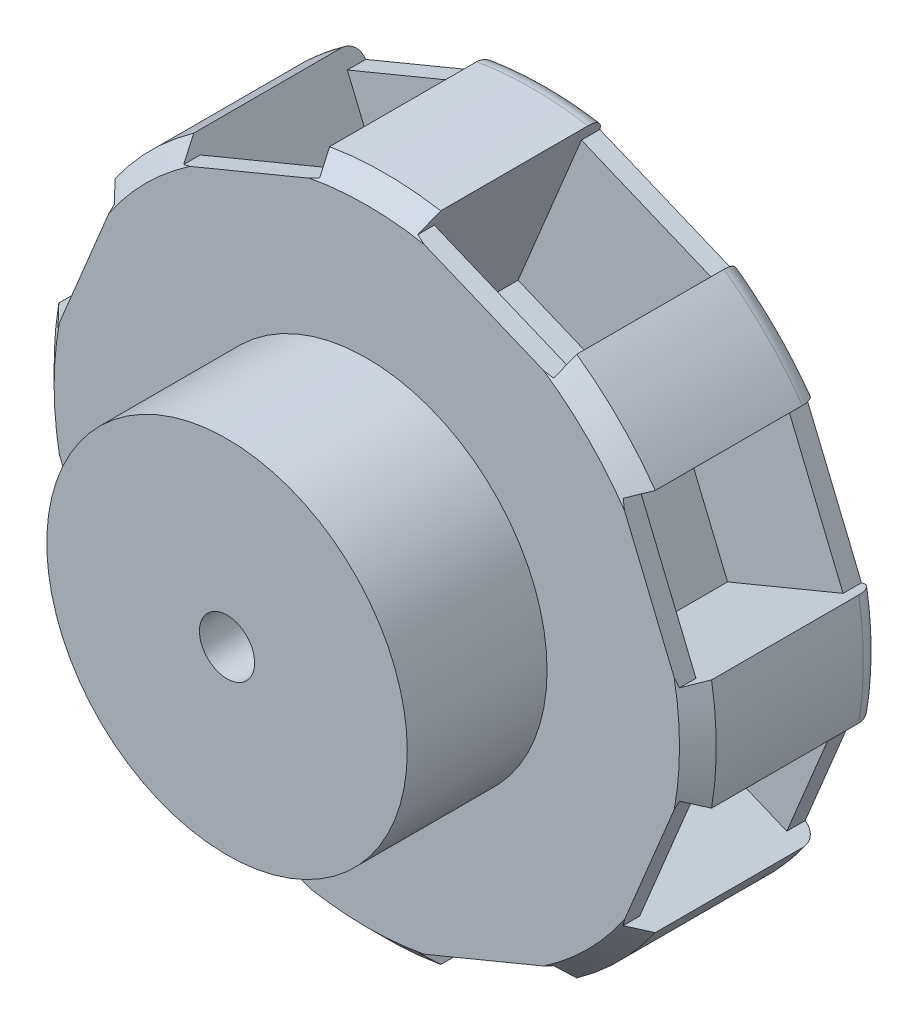
SolidWorks part; units mm, degrees
other "Marca1"
sketch "Croquis12" plane through (-138.4104, -50.431, 0) normal (-0.0114, -0.0085, -0.9999) x (-0.9379, -0.3466, 0.0137)
ref_plane "Alzado" through (0, 0, 0) normal (0, 0, 1) x (1, 0, 0)
ref_plane "Planta" through (0, 0, 0) normal (0, 1, 0) x (1, 0, 0)
ref_plane "Vista lateral" through (0, 0, 0) normal (1, 0, 0) x (0, 0, -1)
sketch "Croquis1" plane through (0, 0, 0) normal (0, 0, 1) x (1, 0, 0)
  circle A0 centre (-48.4104, 39.569) radius 90
  circle A1 centre (-48.4104, 39.569) radius 7.5
  dimension "D1" = 180
  dimension "D2" = 15
extrude "Saliente-Extruir1" add sketch "Croquis1" along normal blind 50
sketch "Croquis2" plane through (0, 0, 50) normal (0, 0, 1) x (1, 0, 0)
  line L6 (-138.4104, 39.569) -> (-112.05, 103.2086) construction
  line L7 (-112.05, 103.2086) -> (-48.4104, 129.569) construction
  line L8 (-48.4104, 129.569) -> (1.8856, 108.7357) construction
  line L9 (15.2292, 103.2086) -> (41.5896, 39.569) construction
  line L10 (41.5896, 39.569) -> (15.2292, -24.0706) construction
  line L11 (15.2292, -24.0706) -> (-48.4104, -50.431) construction
  line L12 (-48.4104, -50.431) -> (-112.05, -24.0706) construction
  line L13 (-112.05, -24.0706) -> (-138.4104, 39.569) construction
  line L14 (-137.1344, 54.6702) -> (-132.8844, 52.9098)
  line L15 (-132.8844, 52.9098) -> (-117.5771, 89.865)
  line L16 (-117.5771, 89.865) -> (-121.8277, 91.6256)
  line L17 (-100.4696, 112.9845) -> (-98.7092, 108.7345)
  line L18 (-98.7092, 108.7345) -> (-61.754, 124.0419)
  line L19 (-61.754, 124.0419) -> (-63.5146, 128.2925)
  line L20 (-35.0696, 124.043) -> (1.8856, 108.7357)
  line L21 (1.8856, 108.7357) -> (3.6463, 112.9863)
  line L22 (-35.0696, 124.043) -> (-33.3092, 128.293)
  line L23 (20.7563, 89.865) -> (36.0637, 52.9098)
  line L24 (36.0637, 52.9098) -> (40.3136, 54.6702)
  line L25 (20.7563, 89.865) -> (25.0069, 91.6256)
  line L26 (40.3131, 24.4647) -> (36.0625, 26.2254)
  line L27 (36.0625, 26.2254) -> (20.7552, -10.7298)
  line L28 (20.7552, -10.7298) -> (25.0052, -12.4902)
  line L29 (-100.467, -33.8484) -> (-98.7064, -29.5978)
  line L30 (-35.0696, -44.9051) -> (1.8856, -29.5978)
  line L31 (1.8856, -29.5978) -> (3.6463, -33.8484)
  line L32 (-35.0696, -44.9051) -> (-33.3092, -49.1551)
  line L33 (-98.7064, -29.5978) -> (-61.7512, -44.9051)
  line L34 (-61.7512, -44.9051) -> (-63.5116, -49.1551)
  line L35 (-132.8833, 26.2254) -> (-137.1339, 24.4647)
  line L36 (-132.8833, 26.2254) -> (-117.5759, -10.7298)
  line L37 (-117.5759, -10.7298) -> (-121.8259, -12.4902)
  circle A0 centre (-48.4104, 39.569) radius 90 construction
  arc A1 (-33.3092, -49.1551) -> (3.6463, -33.8484) centre (-48.4104, 39.569) ccw
  arc A2 (-100.467, -33.8484) -> (-63.5116, -49.1551) centre (-48.4104, 39.569) ccw
  arc A3 (-137.1339, 24.4647) -> (-121.8259, -12.4902) centre (-48.4104, 39.569) ccw
  arc A4 (-121.8277, 91.6256) -> (-137.1344, 54.6702) centre (-48.4104, 39.569) ccw
  arc A5 (-63.5146, 128.2925) -> (-100.4696, 112.9845) centre (-48.4104, 39.569) ccw
  arc A6 (3.6463, 112.9863) -> (-33.3092, 128.293) centre (-48.4104, 39.569) ccw
  arc A7 (40.3136, 54.6702) -> (25.0069, 91.6256) centre (-48.4104, 39.569) ccw
  arc A8 (25.0052, -12.4902) -> (40.3131, 24.4647) centre (-48.4104, 39.569) ccw
  dimension "D5" = 90
  dimension "D6" = 90
  dimension "D7" = 40
  dimension "D8" = 14.44
  dimension "D9" = 14.443
  dimension "D10" = 4.6001
  dimension "D11" = 40
  dimension "D12" = 14.44
  dimension "D13" = 90
  dimension "D14" = 40
  dimension "D15" = 14.44
  dimension "D16" = 90
  dimension "D17" = 90
  dimension "D18" = 40
  dimension "D19" = 14.44
  dimension "D20" = 90
  dimension "D21" = 40
  dimension "D22" = 14.44
  dimension "D23" = 40
  dimension "D24" = 90
  dimension "D25" = 14.44
  dimension "D26" = 90
  dimension "D27" = 90
  dimension "D28" = 40
  dimension "D29" = 40
  dimension "D30" = 14.44
  dimension "D31" = 14.44
extrude "Cortar-Extruir1" cut sketch "Croquis2" against normal blind 50
sketch "Croquis3" plane through (-104.1509, -43.1407, 0) normal (-0.9239, -0.3827, 0) x (0, 0, 1)
  line L0 (0, 75.0813) -> (50, 75.0813) construction
  line L1 (5, 75.0813) -> (45, 75.0813)
  line L2 (5, 75.0813) -> (5, 35.0813)
  line L3 (5, 35.0813) -> (45, 35.0813)
  line L4 (45, 75.0813) -> (45, 35.0813)
  line L6 (0, 35.0813) -> (0, 75.0813) construction
  line L7 (50, 35.0813) -> (50, 75.0813) construction
  dimension "D1" = 40
  dimension "D2" = 40
  dimension "D3" = 0
  dimension "D4" = 5
  dimension "D5" = 5
extrude "Cortar-Extruir2" cut sketch "Croquis3" against normal blind 34
sketch "Croquis4" plane through (-24.9196, -60.1612, 0) normal (-0.3827, -0.9239, 0) x (0.9239, -0.3827, 0)
  line L0 (-79.8662, 0) -> (-79.8662, 50) construction
  line L1 (-79.8662, 45) -> (-39.8662, 45)
  line L2 (-79.8662, 45) -> (-79.8662, 5)
  line L3 (-79.8662, 5) -> (-39.8662, 5)
  line L4 (-39.8662, 45) -> (-39.8662, 5)
  line L5 (-39.8662, 0) -> (-79.8662, 0) construction
  line L8 (-39.8662, 50) -> (-79.8662, 50) construction
  dimension "D1" = 40
  dimension "D2" = 0
  dimension "D3" = 5
  dimension "D4" = 5
extrude "Cortar-Extruir3" cut sketch "Croquis4" against normal blind 45
sketch "Croquis5" plane through (10.7405, -25.9299, 0) normal (0.3827, -0.9239, 0) x (0.9239, 0.3827, 0)
  line L0 (-9.5845, 0) -> (-9.5845, 50) construction
  line L1 (-49.5845, 45) -> (-9.5845, 45)
  line L2 (-49.5845, 45) -> (-49.5845, 5)
  line L3 (-49.5845, 5) -> (-9.5845, 5)
  line L4 (-9.5845, 45) -> (-9.5845, 5)
  line L5 (-9.5845, 0) -> (-49.5845, 0) construction
  line L6 (-9.5845, 50) -> (-49.5845, 50) construction
  dimension "D1" = 40
  dimension "D2" = 0
  dimension "D3" = 5
  dimension "D4" = 5
extrude "Cortar-Extruir4" cut sketch "Croquis5" against normal blind 34
sketch "Croquis6" plane through (21.5092, -8.9094, 0) normal (0.9239, -0.3827, 0) x (0, 0, -1)
  line L0 (0, 38.0296) -> (-50, 38.0296) construction
  line L1 (-45, 38.0296) -> (-5, 38.0296)
  line L2 (-45, 38.0296) -> (-45, -1.9704)
  line L3 (-45, -1.9704) -> (-5, -1.9704)
  line L4 (-5, 38.0296) -> (-5, -1.9704)
  line L5 (0, 38.0296) -> (0, -1.9704) construction
  line L6 (-50, 38.0296) -> (-50, -1.9704) construction
  dimension "D1" = 40
  dimension "D2" = 0
  dimension "D3" = 5
  dimension "D4" = 5
extrude "Cortar-Extruir5" cut sketch "Croquis6" against normal blind 45
sketch "Croquis7" plane through (49.4887, 20.4989, 0) normal (0.9239, 0.3827, 0) x (0, 0, -1)
  line L0 (0, 75.0813) -> (-50, 75.0813) construction
  line L1 (-45, 75.0813) -> (-5, 75.0813)
  line L2 (-45, 75.0813) -> (-45, 35.0813)
  line L3 (-45, 35.0813) -> (-5, 35.0813)
  line L4 (-5, 75.0813) -> (-5, 35.0813)
  line L5 (0, 35.0813) -> (-50, 35.0813) construction
  line L6 (-50, 75.0813) -> (-50, 35.0813) construction
  line L7 (0, 75.0813) -> (0, 35.0813) construction
  dimension "D1" = 5
  dimension "D2" = 5
extrude "Cortar-Extruir6" cut sketch "Croquis7" against normal blind 34
sketch "Croquis9" plane through (38.72, 93.4784, 0) normal (0.3827, 0.9239, 0) x (0.9239, -0.3827, 0)
  line L0 (-79.8693, 0) -> (-79.8693, -50) construction
  line L1 (-79.8693, -5) -> (-39.8693, -5)
  line L2 (-79.8693, -5) -> (-79.8693, -45)
  line L3 (-79.8693, -45) -> (-39.8693, -45)
  line L4 (-39.8693, -5) -> (-39.8693, -45)
  line L5 (-39.8693, 0) -> (-39.8693, -50) construction
  line L6 (-79.8693, -50) -> (-39.8693, -50) construction
  line L7 (-79.8693, 0) -> (-39.8693, 0) construction
  dimension "D1" = 5
  dimension "D2" = 5
extrude "Cortar-Extruir7" cut sketch "Croquis9" against normal blind 45
sketch "Croquis10" plane through (-52.8991, 127.7097, 0) normal (-0.3827, 0.9239, 0) x (0.9239, 0.3827, 0)
  line L0 (-49.5845, 0) -> (-49.5845, -50) construction
  line L1 (-49.5845, -5) -> (-9.5845, -5)
  line L2 (-49.5845, -5) -> (-49.5845, -45)
  line L3 (-49.5845, -45) -> (-9.5845, -45)
  line L4 (-9.5845, -5) -> (-9.5845, -45)
  line L5 (-9.5845, 0) -> (-9.5845, -50) construction
  line L6 (-49.5845, 0) -> (-9.5845, 0) construction
  line L7 (-49.5845, -50) -> (-9.5845, -50) construction
  dimension "D1" = 5
  dimension "D2" = 5
extrude "Cortar-Extruir8" cut sketch "Croquis10" against normal blind 34
sketch "Croquis11" plane through (-132.1304, 54.7302, 0) normal (-0.9239, 0.3827, 0) x (0, 0, 1)
  line L0 (0, 38.0296) -> (50, 38.0296) construction
  line L1 (5, 38.0296) -> (45, 38.0296)
  line L2 (5, 38.0296) -> (5, -1.9704)
  line L3 (5, -1.9704) -> (45, -1.9704)
  line L4 (45, 38.0296) -> (45, -1.9704)
  line L5 (0, -1.9704) -> (50, -1.9704) construction
  line L6 (0, -1.9704) -> (0, 38.0296) construction
  line L7 (50, -1.9704) -> (50, 38.0296) construction
  dimension "D1" = 5
  dimension "D2" = 5
extrude "Cortar-Extruir9" cut sketch "Croquis11" against normal blind 45
sketch "Croquis15" plane through (0, 0, 50) normal (0, 0, 1) x (1, 0, 0)
  circle A0 centre (-48.4104, 39.569) radius 49
  circle A1 centre (-48.4104, 39.569) radius 7.5
  dimension "D1" = 98
extrude "Saliente-Extruir3" add sketch "Croquis15" along normal blind 38
fillet "Redondeo4" radius 5 8 edges at (15.2281, -24.0717, 0) (41.5896, 39.5674, 0) (15.2292, 103.2086, 0) (-48.4119, 129.569, 0) (-112.0511, 103.2075, 0) (-138.4104, 39.5674, 0) (-112.0489, -24.0717, 0) (-48.4104, -50.431, 0)
chamfer "Chaflán1" distance 5 angle 45 8 edges at (41.5896, 39.5674, 50) (15.2292, 103.2086, 50) (-48.4119, 129.569, 50) (-112.0511, 103.2075, 50) (-138.4104, 39.5674, 50) (-112.0489, -24.0717, 50) (-48.4104, -50.431, 50) (15.2281, -24.0717, 50)
